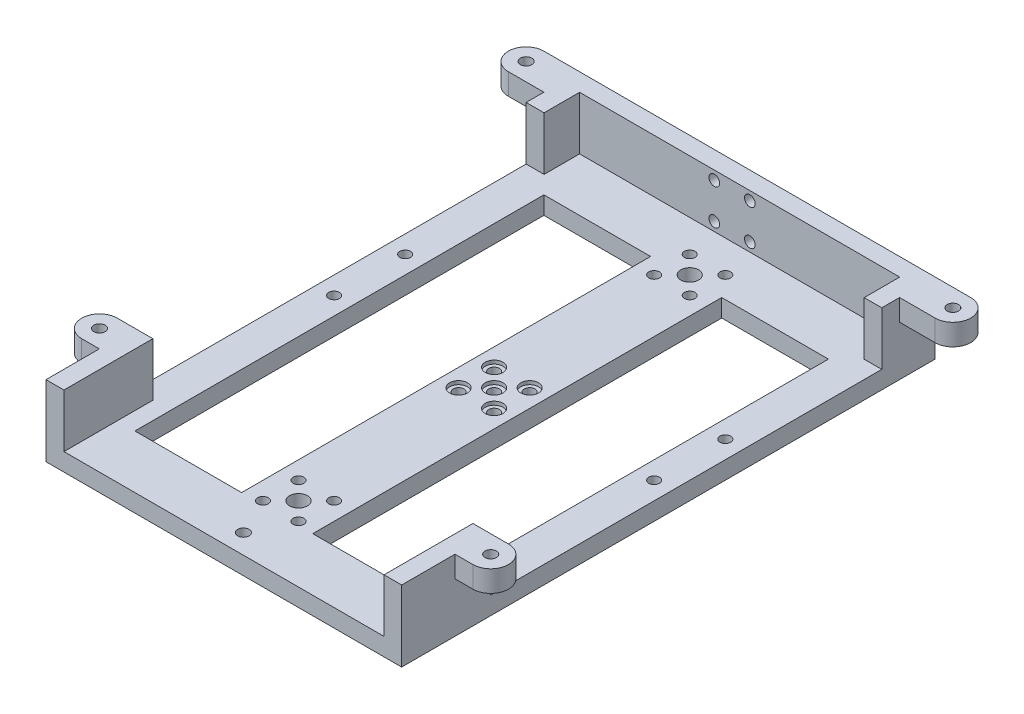
SolidWorks part; units mm, degrees
ref_plane "Front" through (0, 0, 0) normal (0, 0, 1) x (1, 0, 0)
ref_plane "Top" through (0, 0, 0) normal (0, 1, 0) x (1, 0, 0)
ref_plane "Right" through (0, 0, 0) normal (1, 0, 0) x (0, 0, -1)
sketch "草图2" plane through (0, 0, 0) normal (0, 0, 1) x (1, 0, 0)
  line L1 (-50, 20) -> (50, 20)
  line L2 (-50, 20) -> (-50, -20)
  line L3 (-50, -20) -> (50, -20)
  line L4 (50, 20) -> (50, -20)
  line L5 (-50, 20) -> (50, -20) construction
  line L6 (-50, -20) -> (50, 20) construction
  point P0 (0, 0)
  dimension "D1" = 100
  dimension "D2" = 40
extrude "凸台-拉伸1" add sketch "草图2" along normal blind 150
sketch "草图3" plane through (0, 0, 150) normal (0, 0, 1) x (1, 0, 0)
  line L0 (50, 20) -> (-50, 20) construction
  line L1 (-44.9554, 17) -> (45.0446, 17)
  line L2 (-44.9554, 17) -> (-44.9554, -15)
  line L3 (-44.9554, -15) -> (45.0446, -15)
  line L4 (45.0446, 17) -> (45.0446, -15)
  line L8 (-50, -20) -> (50, -20) construction
  point P0 (0, 0)
  dimension "D1" = 90
  dimension "D2" = 3
  dimension "D3" = 5
extrude "切除-拉伸1" cut sketch "草图3" against normal blind 145
sketch "草图4" plane through (0, -20, 0) normal (0, -1, 0) x (1, 0, 0)
  line L0 (-50, 150) -> (50, 150) construction
  line L1 (-40, 135) -> (-10, 135)
  line L2 (-40, 135) -> (-40, 20)
  line L3 (-40, 20) -> (-10, 20)
  line L4 (-10, 135) -> (-10, 20)
  line L5 (10, 135) -> (40, 135)
  line L6 (10, 135) -> (10, 20)
  line L7 (10, 20) -> (40, 20)
  line L8 (40, 135) -> (40, 20)
  line L9 (-50, 0) -> (50, 0) construction
  line L10 (-50, 150) -> (-50, 0) construction
  line L11 (50, 150) -> (50, 0) construction
  dimension "D1" = 15
  dimension "D2" = 20
  dimension "D3" = 20
  dimension "D4" = 15
  dimension "D5" = 10
  dimension "D6" = 10
  dimension "D7" = 30
  dimension "D8" = 30
extrude "切除-拉伸2" cut sketch "草图4" against normal blind 20
sketch "草图5" plane through (0, 20, 0) normal (0, 1, 0) x (1, 0, 0)
  line L0 (50, 0) -> (-50, 0) construction
  line L1 (-40, -20) -> (-5, -20)
  line L2 (-40, -20) -> (-40, -135)
  line L3 (-40, -135) -> (-5, -135)
  line L4 (-5, -20) -> (-5, -135)
  line L5 (5, -20) -> (40, -20)
  line L6 (5, -20) -> (5, -135)
  line L7 (5, -135) -> (40, -135)
  line L8 (40, -20) -> (40, -135)
  line L9 (-50, -150) -> (-50, 0) construction
  line L10 (50, -150) -> (50, 0) construction
  line L11 (50, -150) -> (-50, -150) construction
  dimension "D1" = 20
  dimension "D2" = 20
  dimension "D3" = 10
  dimension "D4" = 10
  dimension "D5" = 15
  dimension "D6" = 15
  dimension "D7" = 35
  dimension "D8" = 35
extrude "切除-拉伸3" cut sketch "草图5" against normal blind 20
sketch "草图6" plane through (-50, 0, 0) normal (-1, 0, 0) x (0, 0, 1)
  line L0 (150, 20) -> (0, 20) construction
  line L1 (15, 16) -> (135, 16)
  line L2 (15, 16) -> (15, -15)
  line L3 (15, -15) -> (135, -15)
  line L4 (135, 16) -> (135, -15)
  line L5 (150, -20) -> (0, -20) construction
  line L6 (150, 20) -> (150, -20) construction
  line L7 (0, 20) -> (0, -20) construction
  dimension "D1" = 4
  dimension "D2" = 5
  dimension "D3" = 15
  dimension "D4" = 15
extrude "切除-拉伸4" cut sketch "草图6" against normal blind 207
sketch "草图7" plane through (0, -20, 0) normal (0, -1, 0) x (1, 0, 0)
  line L1 (-10, 20) -> (-10, 135) construction
  line L2 (-50, 150) -> (50, 150) construction
  circle A0 centre (-5, 134) radius 1.5
  circle A1 centre (5, 134) radius 1.5
  circle A2 centre (5, 124) radius 1.5
  circle A3 centre (-5, 124) radius 1.5
  dimension "D1" = 3
  dimension "D2" = 3
  dimension "D3" = 3
  dimension "D4" = 3
  dimension "D5" = 10
  dimension "D6" = 10
  dimension "D7" = 10
  dimension "D8" = 5
  dimension "D9" = 5
  dimension "D10" = 16
  dimension "D11" = 16
  dimension "D12" = 10
extrude "切除-拉伸5" cut sketch "草图7" against normal blind 15
sketch "草图8" plane through (0, -20, 0) normal (0, -1, 0) x (1, 0, 0)
  circle A0 centre (0, 129) radius 2.5
  circle A1 centre (5, 134) radius 1.5 construction
  dimension "D1" = 5
  dimension "D2" = 5
extrude "切除-拉伸6" cut sketch "草图8" against normal blind 15
sketch "草图11" plane through (0, 20, 0) normal (0, 1, 0) x (1, 0, 0)
  line L1 (-50, 0) -> (50, 0)
  line L2 (-50, 0) -> (-50, -150)
  line L3 (-50, -150) -> (50, -150)
  line L4 (50, 0) -> (50, -150)
extrude "切除-拉伸7" cut sketch "草图11" against normal blind 20
sketch "草图12" plane through (0, 0, 0) normal (0, 1, 0) x (1, 0, 0)
  line L0 (-50, 0) -> (-60, 0)
  line L1 (50, 0) -> (50, -10)
  line L2 (-60, -10) -> (-50, -10)
  line L3 (-50, 0) -> (-50, -15) construction
  line L4 (50, 0) -> (60, 0)
  line L6 (60, -10) -> (50, -10)
  line L7 (50, -15) -> (50, 0) construction
  line L9 (-50, -10) -> (-50, 0)
  line L11 (45.0446, -125) -> (45.0446, -135)
  line L13 (45.0446, -135) -> (55.0446, -135)
  line L15 (45.0446, -125) -> (55.0446, -125)
  line L17 (-44.9554, -125) -> (-44.9554, -135)
  line L18 (-44.9554, -135) -> (-54.9554, -135)
  line L19 (-44.9554, -125) -> (-54.9554, -125)
  arc A0 (-60, 0) -> (-60, -10) centre (-60, -5) ccw
  arc A1 (60, -10) -> (60, 0) centre (60, -5) ccw
  circle A4 centre (-60, -5) radius 1.6
  circle A5 centre (60, -5) radius 1.6
  arc A8 (55.0446, -135) -> (55.0446, -125) centre (55.0446, -130) ccw
  circle A9 centre (55.0446, -130) radius 1.6
  arc A10 (-54.9554, -125) -> (-54.9554, -135) centre (-54.9554, -130) ccw
  circle A11 centre (-54.9554, -130) radius 1.6
  dimension "D6" = 3.2
  dimension "D7" = 3.2
  dimension "D12" = 3.2
  dimension "D1" = 10
  dimension "D2" = 10
  dimension "D10" = 10
  dimension "D11" = 10
extrude "凸台-拉伸3" add sketch "草图12" against normal blind 6
sketch "草图13" plane through (0, -6, 0) normal (0, -1, 0) x (1, 0, 0)
  line L1 (50, 135) -> (45.0446, 135)
  line L2 (50, 135) -> (50, 125)
  line L3 (50, 125) -> (45.0446, 125)
  line L4 (45.0446, 135) -> (45.0446, 125)
  line L5 (-50, 135) -> (-44.9554, 135)
  line L6 (-50, 135) -> (-50, 125)
  line L7 (-50, 125) -> (-44.9554, 125)
  line L8 (-44.9554, 135) -> (-44.9554, 125)
extrude "凸台-拉伸4" add sketch "草图13" along normal blind 10
sketch "草图15" plane through (0, -20, 0) normal (0, -1, 0) x (1, 0, 0)
  line L0 (-50, 150) -> (50, 150) construction
  circle A0 centre (0, 144.5) radius 1.6
  point P4 (0, 150)
  dimension "D1" = 3.2
  dimension "D2" = 5.5
extrude "切除-拉伸8" cut sketch "草图15" against normal blind 10
sketch "草图16" plane through (0, -15, 0) normal (0, 1, 0) x (1, 0, 0)
  line L1 (5, -24) -> (-5, -24) construction
  line L2 (5, -24) -> (5, -14) construction
  line L3 (5, -14) -> (-5, -14) construction
  line L4 (-5, -24) -> (-5, -14) construction
  line L5 (5, -24) -> (-5, -14) construction
  line L6 (5, -14) -> (-5, -24) construction
  line L7 (5, -79) -> (-5, -79) construction
  line L8 (5, -79) -> (5, -69) construction
  line L9 (5, -69) -> (-5, -69) construction
  line L10 (-5, -79) -> (-5, -69) construction
  line L11 (5, -79) -> (-5, -69) construction
  line L12 (5, -69) -> (-5, -79) construction
  circle A0 centre (0, -74) radius 1.5
  circle A1 centre (0, -19) radius 2.5
  circle A2 centre (0, -129) radius 2.5 construction
  circle A3 centre (-5, -14) radius 1.5
  circle A4 centre (5, -14) radius 1.5
  circle A5 centre (-5, -24) radius 1.5
  circle A6 centre (5, -24) radius 1.5
  circle A7 centre (-5, -69) radius 1.5
  circle A8 centre (5, -69) radius 1.5
  circle A9 centre (5, -79) radius 1.5
  circle A10 centre (-5, -79) radius 1.5
  dimension "D1" = 55
  dimension "D3" = 5
  dimension "D4" = 3
  dimension "D9" = 3
  dimension "D10" = 3
  dimension "D11" = 3
  dimension "D12" = 3
  dimension "D13" = 3
  dimension "D14" = 3
  dimension "D15" = 3
  dimension "D16" = 3
  dimension "D2" = 55
  dimension "D5" = 10
  dimension "D6" = 10
  dimension "D7" = 10
  dimension "D8" = 10
extrude "切除-拉伸9" cut sketch "草图16" against normal blind 10
sketch "草图17" plane through (0, -20, 0) normal (0, -1, 0) x (1, 0, 0)
  line L0 (-40, 135) -> (-40, 20) construction
  line L1 (0, 74) -> (0, 85.2545) construction
  circle A0 centre (-45, 74) radius 1.5
  circle A1 centre (-45, 54) radius 1.5
  circle A2 centre (0, 74) radius 1.5 construction
  circle A3 centre (45, 54) radius 1.5
  circle A4 centre (45, 74) radius 1.5
  dimension "D1" = 3
  dimension "D2" = 3
  dimension "D3" = 20
  dimension "D4" = 5
  dimension "D5" = 0
extrude "切除-拉伸10" cut sketch "草图17" against normal blind 10
sketch "草图18" plane through (0, 0, 5) normal (0, 0, 1) x (1, 0, 0)
  line L0 (-50, -20) -> (50, -20) construction
  circle A0 centre (-7.0897, -2.5) radius 1.5
  circle A1 centre (2.9103, -2.5) radius 1.5
  circle A2 centre (-7.0897, -12.5) radius 1.5
  circle A3 centre (2.9103, -12.5) radius 1.5
  dimension "D1" = 3
  dimension "D2" = 3
  dimension "D3" = 3
  dimension "D4" = 3
  dimension "D5" = 10
  dimension "D6" = 10
  dimension "D7" = 7.5
extrude "切除-拉伸11" cut sketch "草图18" against normal blind 10
sketch "草图19" plane through (0, -15, 0) normal (0, 1, 0) x (1, 0, 0)
  circle A0 centre (5, -79) radius 2.5
  circle A1 centre (-5, -79) radius 2.5
  circle A2 centre (-5, -69) radius 2.5
  circle A3 centre (5, -69) radius 2.5
  dimension "D1" = 5
  dimension "D2" = 5
  dimension "D3" = 5
  dimension "D4" = 5
extrude "切除-拉伸12" cut sketch "草图19" against normal blind 1
sketch "草图20" plane through (0, -15, 0) normal (0, 1, 0) x (1, 0, 0)
  circle A0 centre (0, -74) radius 2.5
  dimension "D1" = 5
extrude "切除-拉伸13" cut sketch "草图20" against normal blind 1
